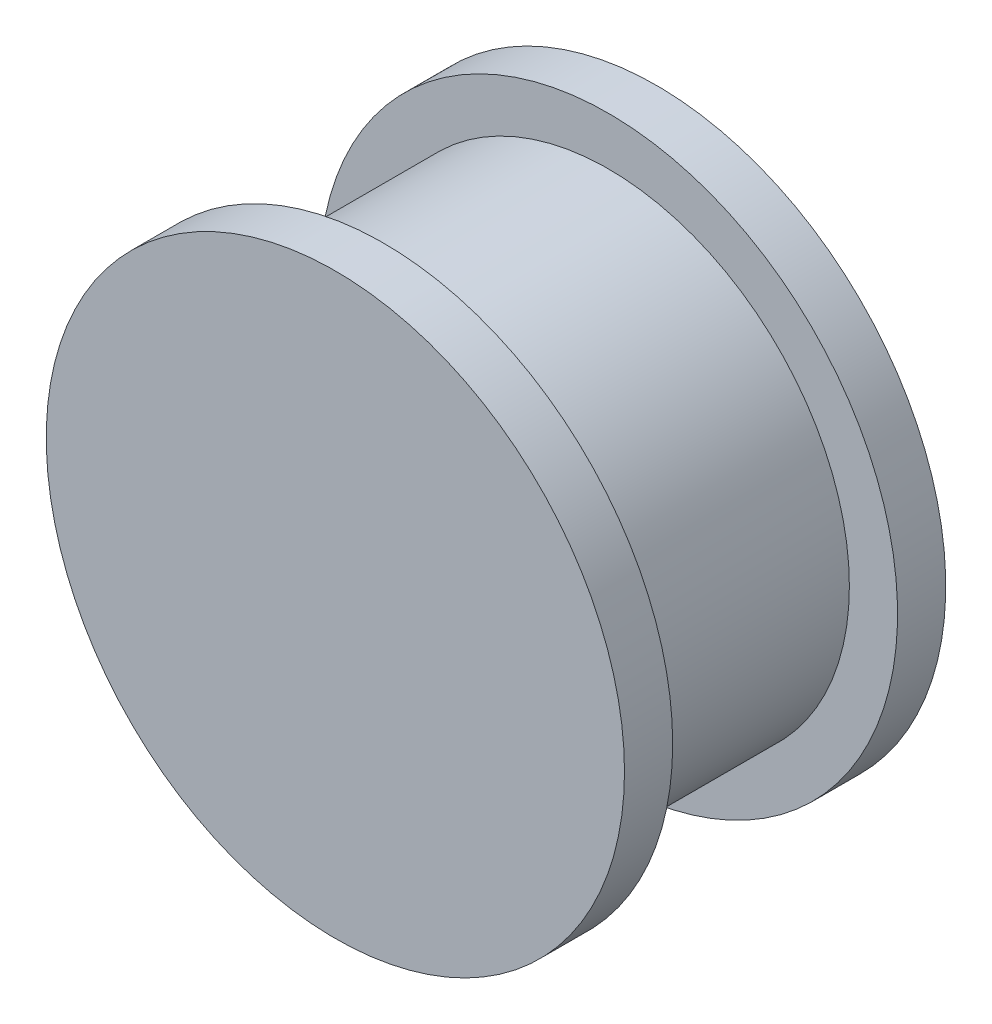
SolidWorks part; units mm, degrees
ref_plane "Front Plane" through (0, 0, 0) normal (0, 0, 1) x (1, 0, 0)
ref_plane "Top Plane" through (0, 0, 0) normal (0, 1, 0) x (1, 0, 0)
ref_plane "Right Plane" through (0, 0, 0) normal (1, 0, 0) x (0, 0, -1)
sketch "Sketch1" plane through (0, 0, 0) normal (0, 0, 1) x (1, 0, 0)
  circle A0 centre (0, 0) radius 6.5
  circle A1 centre (0, 0) radius 7.5
  dimension "D1" = 13
  dimension "D2" = 1
extrude "Boss-Extrude2" add sketch "Sketch1" along normal blind 7
sketch "Sketch3" plane through (0, 0, 7) normal (0, 0, 1) x (1, 0, 0)
  circle A0 centre (0, 0) radius 9
  dimension "D1" = 18
extrude "Boss-Extrude3" add sketch "Sketch3" along normal blind 1.5
sketch "Sketch4" plane through (0, 0, 0) normal (0, 0, -1) x (-1, 0, 0)
  circle A0 centre (0, 0) radius 6.5
  circle A1 centre (0, 0) radius 9
  circle A2 centre (0, 0) radius 6.5 construction
extrude "Boss-Extrude4" add sketch "Sketch4" along normal blind 1.5 separate body
sketch "Sketch5" plane through (0, 0, 7) normal (0, 0, -1) x (-1, 0, 0)
  circle A0 centre (0, 0) radius 6.5
extrude "Boss-Extrude5" add sketch "Sketch5" along normal blind 1
